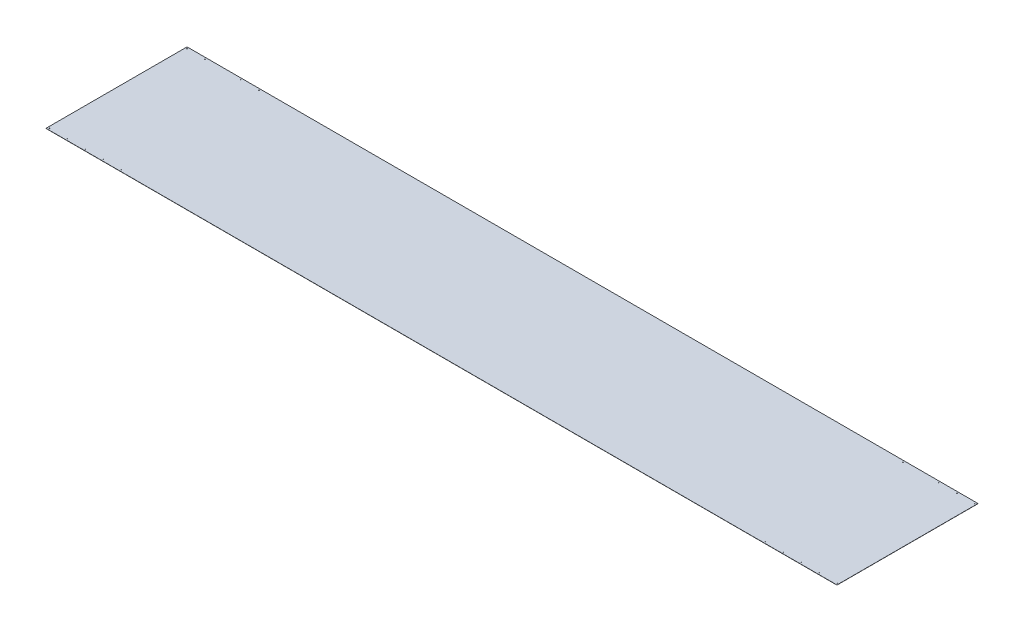
SolidWorks part; units mm, degrees
material "5052-H32"
ref_plane "Front Plane" through (0, 0, 0) normal (0, 0, 1) x (1, 0, 0)
ref_plane "Top Plane" through (0, 0, 0) normal (0, 1, 0) x (1, 0, 0)
ref_plane "Right Plane" through (0, 0, 0) normal (1, 0, 0) x (0, 0, -1)
sketch "Sketch1" plane through (0, 0, 0) normal (0, 1, 0) x (1, 0, 0)
  line L1 (4679.25, -834.5) -> (-4679.25, -834.5)
  line L2 (4679.25, -834.5) -> (4679.25, 834.5)
  line L3 (4679.25, 834.5) -> (-4679.25, 834.5)
  line L4 (-4679.25, -834.5) -> (-4679.25, 834.5)
  line L5 (4679.25, -834.5) -> (-4679.25, 834.5) construction
  line L6 (4679.25, 834.5) -> (-4679.25, -834.5) construction
  point P0 (0, 0)
  dimension "D1" = 1669
  dimension "D2" = 9358.5
extrude "Boss-Extrude1" add sketch "Sketch1" along normal blind 2
sketch "Sketch3" plane through (0, 2, 0) normal (0, 1, 0) x (1, 0, 0)
  line L0 (-4679.25, 834.5) -> (-4679.25, -834.5) construction
  line L1 (4679.25, 834.5) -> (-4679.25, 834.5) construction
  line L2 (-4679.25, -834.5) -> (4679.25, -834.5) construction
  line L3 (4679.25, -834.5) -> (4679.25, 834.5) construction
  circle A0 centre (-4659.25, 814.5) radius 3.25
  circle A1 centre (-4659.25, -814.5) radius 3.25
  circle A2 centre (-4446.75, 814.5) radius 3.25
  circle A3 centre (-4446.75, -814.5) radius 3.25
  circle A4 centre (-4234.25, 814.5) radius 3.25
  circle A5 centre (-4234.25, -814.5) radius 3.25
  circle A6 centre (-4021.75, 814.5) radius 3.25
  circle A7 centre (-4021.75, -814.5) radius 3.25
  circle A8 centre (-3809.25, 814.5) radius 3.25
  circle A9 centre (-3809.25, -814.5) radius 3.25
  circle A10 centre (4662.25, 814.5) radius 3.25
  circle A11 centre (4662.25, -814.5) radius 3.25
  circle A12 centre (4449.75, 814.5) radius 3.25
  circle A13 centre (4449.75, -814.5) radius 3.25
  circle A14 centre (4237.25, 814.5) radius 3.25
  circle A15 centre (4237.25, -814.5) radius 3.25
  circle A16 centre (4024.75, 814.5) radius 3.25
  circle A17 centre (4024.75, -814.5) radius 3.25
  circle A18 centre (3812.25, 814.5) radius 3.25
  circle A19 centre (3812.25, -814.5) radius 3.25
  dimension "D2" = 6.5
  dimension "D9" = 6.5
  dimension "D1" = 20
  dimension "D3" = 20
  dimension "D4" = 20
  dimension "D6" = 20
  dimension "D7" = 20
  dimension "D8" = 17
  dimension "D11" = 212.5
  dimension "D12" = 212.5
  dimension "D5" = 5
  dimension "D10" = 5
extrude "Cut-Extrude1" cut sketch "Sketch3" against normal blind 10
